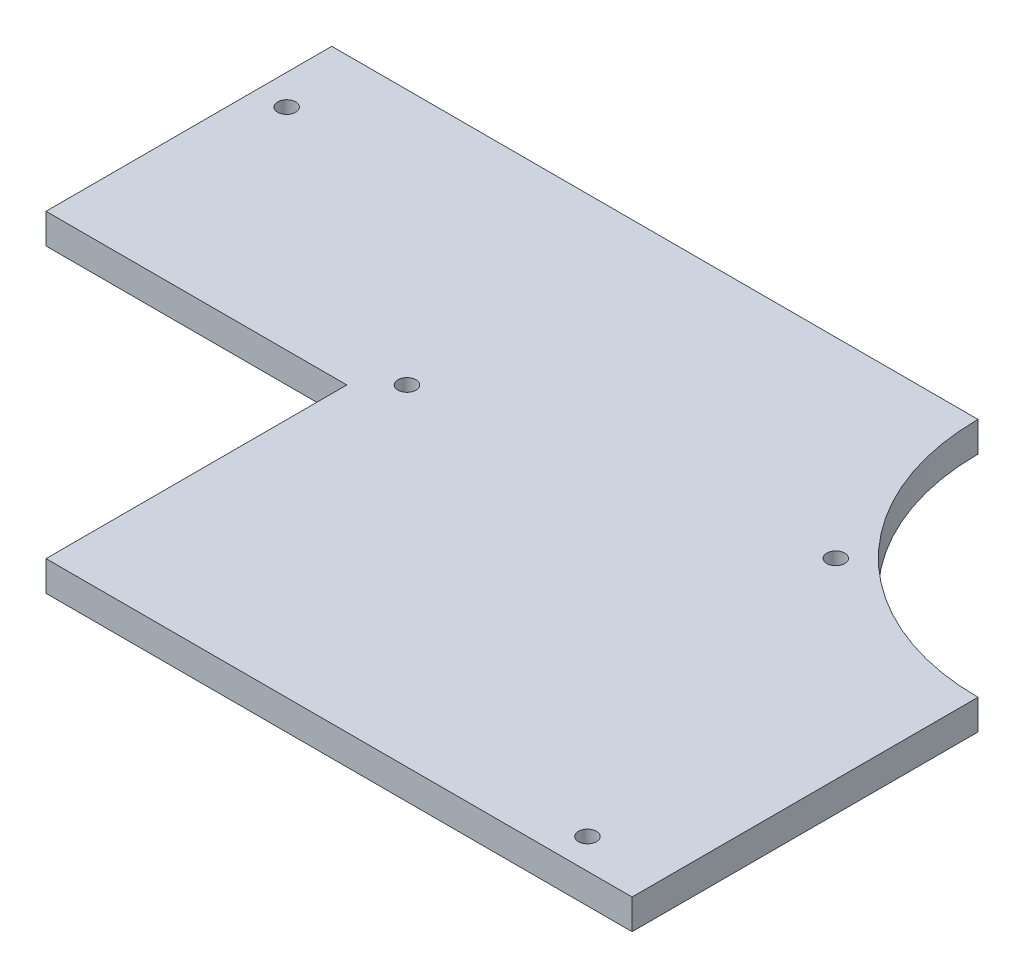
SolidWorks part; units mm, degrees
ref_plane "Plan de face" through (0, 0, 0) normal (0, 0, 1) x (1, 0, 0)
ref_plane "Plan de dessus" through (0, 0, 0) normal (0, 1, 0) x (1, 0, 0)
ref_plane "Plan de droite" through (0, 0, 0) normal (1, 0, 0) x (0, 0, -1)
sketch "Esquisse1" plane through (0, 0, 0) normal (0, 1, 0) x (1, 0, 0)
  line L1 (0, -97.415) -> (-97.415, -97.415)
  line L4 (-147.415, -47.415) -> (-147.415, 2.585)
  line L9 (-147.415, 2.585) -> (-142.415, 2.585) construction
  line L14 (-147.415, -47.415) -> (-97.415, -47.415)
  line L15 (-97.415, -47.415) -> (-97.415, -97.415)
  line L16 (-92.415, -92.415) -> (-3.9118, -92.415) construction
  line L17 (-147.415, -42.415) -> (-92.415, -42.415) construction
  line L18 (-92.415, -42.415) -> (-92.415, -97.415) construction
  line L19 (0, 0.085) -> (-31.8198, -31.7348) construction
  line L20 (-147.415, 0.085) -> (0, 0.085)
  line L21 (0, -97.415) -> (0, 0.085)
  line L27 (-142.415, 2.585) -> (-142.415, -47.415) construction
  circle A3 centre (-142.415, -42.415) radius 1.5 construction
  circle A4 centre (-92.415, -42.415) radius 1.5
  circle A5 centre (-92.415, -92.415) radius 1.5 construction
  circle A14 centre (-142.415, -12.415) radius 1.5
  circle A15 centre (-12.415, -92.415) radius 1.5
  arc A16 (-40, 0.085) -> (0, -39.915) centre (0, 0.085) ccw
  circle A18 centre (-31.8198, -31.7348) radius 1.5
  point P0 (0, 0)
  dimension "D7" = 30
  dimension "D2" = 3
  dimension "D12" = 40
  dimension "D3" = 45
  dimension "D4" = 5
  dimension "D5" = 5
  dimension "D6" = 5
  dimension "D8" = 80
  dimension "D9" = 5
  dimension "D10" = 50
  dimension "D11" = 97.415
  dimension "D13" = 45
  dimension "D15" = 5
extrude "Boss.-Extru.1" add sketch "Esquisse1" along normal blind 5
